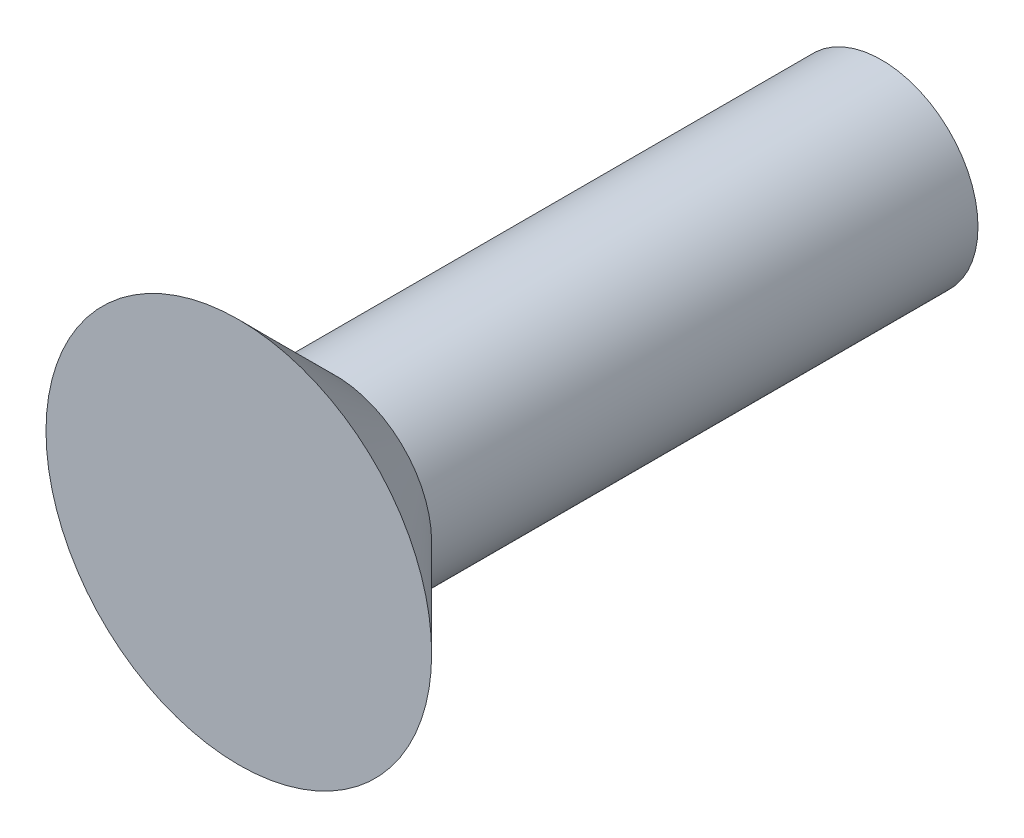
SolidWorks part; units mm, degrees
ref_plane "前视基准面" through (0, 0, 0) normal (0, 0, 1) x (1, 0, 0)
ref_plane "上视基准面" through (0, 0, 0) normal (0, 1, 0) x (1, 0, 0)
ref_plane "右视基准面" through (0, 0, 0) normal (1, 0, 0) x (0, 0, -1)
other "Configuration Table"
sketch "Sketch_Nominal_shank" plane through (0, 0, 0) normal (0, 0, 1) x (1, 0, 0)
  circle A0 centre (0, 0) radius 1.5
  dimension "D1" = 3
extrude "Nominal_shank" add sketch "Sketch_Nominal_shank" along normal blind 8.5 from offset 10
sketch "Sketch_Head" plane through (0, 0, 0) normal (0, 0, 1) x (1, 0, 0)
  circle A0 centre (0, 0) radius 1.5
  dimension "D1" = 3
extrude "Head" add sketch "Sketch_Head" along normal blind 1.5 draft 45 from offset 1.5
